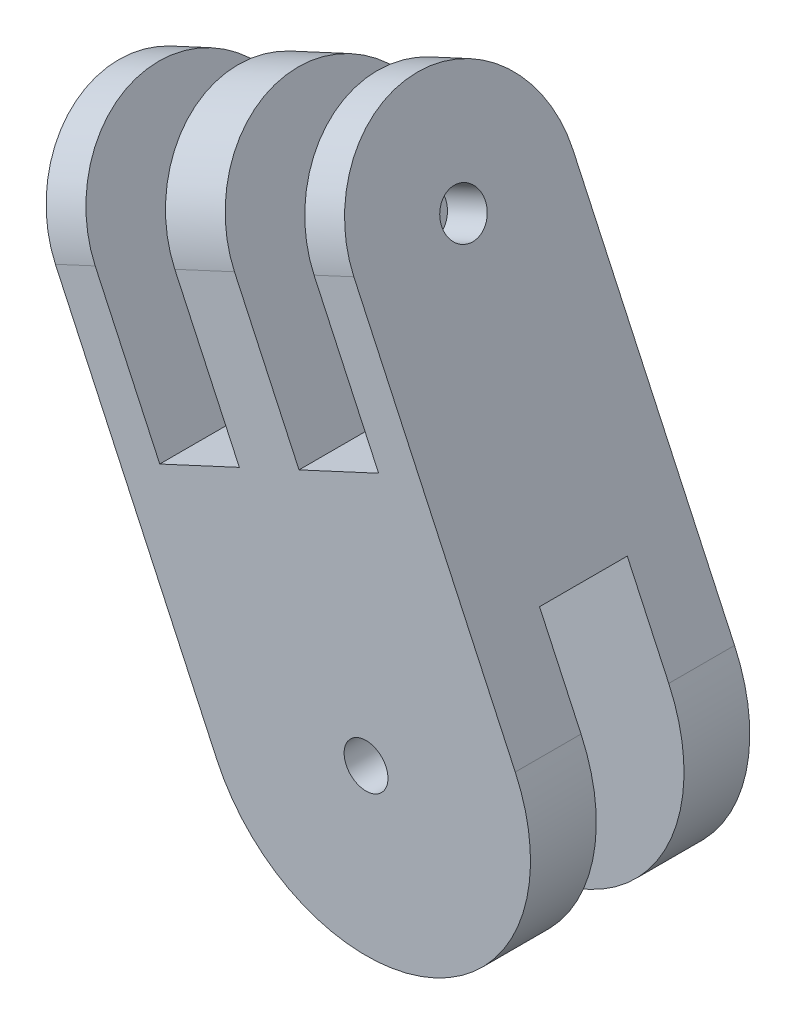
SolidWorks part; units mm, degrees
ref_plane "Plan de face" through (0, 0, 0) normal (0, 0, 1) x (1, 0, 0)
ref_plane "Plan de dessus" through (0, 0, 0) normal (0, 1, 0) x (1, 0, 0)
ref_plane "Plan de droite" through (0, 0, 0) normal (1, 0, 0) x (0, 0, -1)
sketch "Esquisse1" plane through (0, 0, 0) normal (0, 0, 1) x (1, 0, 0)
  line L0 (-74.7016, 52.3094) -> (-61.0927, 58.6179)
  line L1 (-61.0927, 58.6179) -> (-73.7097, 85.8358)
  line L2 (-73.7097, 85.8358) -> (-87.3186, 79.5273)
  line L3 (-87.3186, 79.5273) -> (-74.7016, 52.3094)
  line L4 (-75.5242, 84.9947) -> (-70.4774, 74.1075)
  line L5 (-70.4774, 74.1075) -> (-74.1065, 72.4253)
  line L6 (-74.1065, 72.4253) -> (-79.1533, 83.3124)
  line L7 (-79.1533, 83.3124) -> (-81.8751, 82.0507)
  line L8 (-81.8751, 82.0507) -> (-76.8283, 71.1636)
  line L9 (-76.8283, 71.1636) -> (-80.4573, 69.4813)
  line L10 (-80.4573, 69.4813) -> (-85.5041, 80.3684)
  line L11 (-87.3186, 79.5273) -> (-61.0927, 58.6179) construction
  line L12 (-61.0927, 58.6179) -> (-73.7097, 85.8358) construction
  line L13 (-74.7016, 52.3094) -> (-73.7097, 85.8358) construction
  line L14 (-78.4113, 78.1452) -> (-70, 60) construction
  line L15 (-77.8559, 59.1139) -> (-64.247, 65.4224)
  arc A0 (-64.247, 65.4224) -> (-77.8559, 59.1139) centre (-71.0514, 62.2682) cw
  circle A1 centre (-71.0514, 62.2682) radius 1
  point P6 (-74.2057, 69.0726)
  point P15 (-74.2057, 69.0726)
  point P17 (-78.6428, 70.3224)
  point P23 (-71.0514, 62.2682)
  dimension "D10" = 2
  dimension "D1" = 3
  dimension "D2" = 2
  dimension "D3" = 2
  dimension "D4" = 15
  dimension "D5" = 4
  dimension "D6" = 5
  dimension "D7" = 12
  dimension "D8" = 12
  dimension "D9" = 7.5
extrude "Boss.-Extru.1" add sketch "Esquisse1" along normal blind 10 contours A1 L15 A0 | A1 L15 L1 L2 L4 L5 L6 L8 L9 L10 L3
sketch "Esquisse2" plane through (-41.5293, -19.2512, 0) normal (-0.9073, -0.4206, 0) x (0, 0, 1)
  line L0 (0, 108.8754) -> (10, 108.8754)
  line L1 (10, 108.8754) -> (10, 86.3754) construction
  line L2 (10, 108.8754) -> (0, 108.8754) construction
  line L3 (10, 108.8754) -> (10, 78.8754)
  line L4 (10, 78.8754) -> (0, 78.8754)
  line L5 (0, 78.8754) -> (0, 108.8754)
  line L6 (0, 103.8754) -> (10, 103.8754)
  line L7 (3, 78.8754) -> (3, 90.8754)
  line L8 (3, 90.8754) -> (7, 90.8754)
  line L9 (7, 90.8754) -> (7, 78.8754)
  arc A0 (0, 103.8754) -> (10, 103.8754) centre (5, 103.8754) cw
  circle A1 centre (5, 103.8754) radius 1
  point P13 (5, 78.8754)
  line M8 (0, 108.8754) -> (0, 86.3754)
  line M9 (0, 86.3754) -> (10, 86.3754)
  line M11 (10, 108.8754) -> (0, 108.8754)
  dimension "D6" = 2
  dimension "D1" = 30
  dimension "D2" = 5
  dimension "D3" = 3
  dimension "D4" = 4
  dimension "D5" = 12
extrude "Enlèv. mat.-Extru.1" cut sketch "Esquisse2" against normal blind 15 contours A0 L0 M8 | A0 L3 M11 | L6 A1 | L6 A1 | L9 L7 L4 M9 | L9 L8 L7 M9
